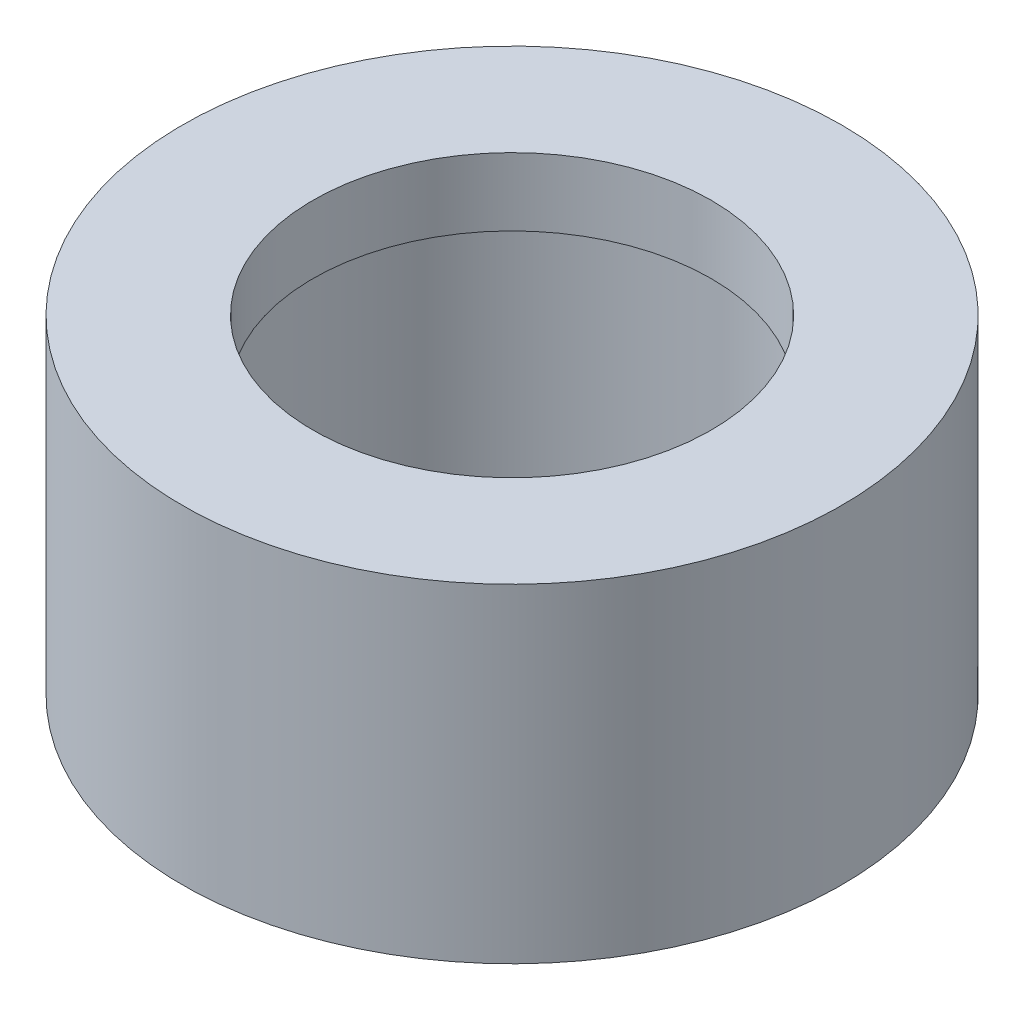
SolidWorks part; units mm, degrees
ref_plane "Front Plane" through (0, 0, 0) normal (0, 0, 1) x (1, 0, 0)
ref_plane "Top Plane" through (0, 0, 0) normal (0, 1, 0) x (1, 0, 0)
ref_plane "Right Plane" through (0, 0, 0) normal (1, 0, 0) x (0, 0, -1)
sketch "Sketch1" plane through (0, 0, 0) normal (1, 0, 0) x (0, 0, -1)
  line L0 (0, 0) -> (9.695, 0) construction
  line L1 (0, 0) -> (0, 13.4125) construction
  line L2 (9.695, 0) -> (9.695, 3.302)
  line L3 (9.695, 3.302) -> (16.045, 3.302)
  line L4 (16.045, 3.302) -> (16.045, -12.7)
  line L5 (16.045, -12.7) -> (11.2825, -12.7)
  line L10 (11.2825, -12.7) -> (11.2825, 0)
  line L11 (11.2825, 0) -> (9.695, 0)
  dimension "D1" = 3.302
  dimension "D2" = 6.35
  dimension "D3" = 12.7
  dimension "D5" = 1.5875
revolve "Revolve1" add sketch "Sketch1" angle 360 about L1
